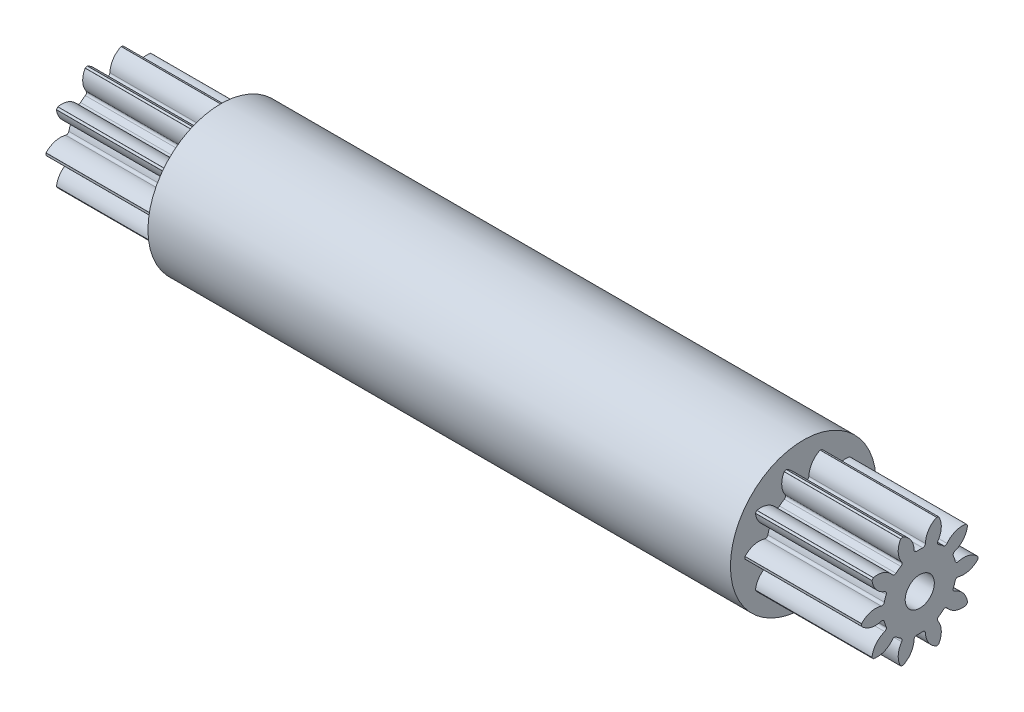
SolidWorks part; units mm, degrees
ref_plane "Plane1" through (0, 0, 0) normal (0, 0, 1) x (1, 0, 0)
ref_plane "Plane2" through (0, 0, 0) normal (0, 1, 0) x (1, 0, 0)
ref_plane "Plane3" through (0, 0, 0) normal (1, 0, 0) x (0, 0, -1)
sketch "HoldingSke" plane through (0, 0, 0) normal (0, 1, 0) x (1, 0, 0)
  line L0 (0, 0) -> (0.9848, -0.1736)
  line L1 (-15, 0) -> (100, 0) construction
  line L2 (0, 0) -> (-2.1039, 2.3779)
  line L3 (0, 0) -> (-11.863, 4.5341)
  line L4 (0, 0) -> (8.5048, 1.4996)
  line L5 (0, 0) -> (-46.8476, -17.4728)
  line L6 (0, 0) -> (-9.9476, -6.7116)
  line L7 (-2.1039, 2.3779) -> (8.6586, 51.2059)
  line L8 (-76.2, 54.61) -> (-76.1, 54.61)
  line L9 (-71.009, 38.7566) -> (-53.1078, 45.2721)
  line L10 (-76.2, 71.12) -> (104.1128, 71.12)
  line L11 (0, 0) -> (-12, 0)
  line L12 (-76.2, 101.6) -> (-76.162, 101.6)
  line L13 (24.9733, 27.94) -> (52.9518, 28.4284)
  line L14 (24.9733, 27.94) -> (24.9743, 27.94)
  line L15 (24.9733, 27.94) -> (100.4006, 29.5858)
  line L16 (-63.627, -1) -> (-12.827, -1)
  circle A0 centre (0, 0) radius 0.4
  circle A1 centre (0, 0) radius 3.749
  circle A2 centre (0, 0) radius 37.5
  circle A3 centre (0, 0) radius 0.4
  dimension "MHD" = 7.498
  dimension "Hub_dia" = 75
  dimension "Bore" = 0.8
  dimension "MBD" = 0.8
  dimension "Num_teeth" = 10
  dimension "Pitch" = 1
  dimension "Overall_len" = 50
  dimension "Show_teeth" = 10
  dimension "Thickness" = 12
  dimension "OAL" = 50.0001
  dimension "T_dim" = 0.1
  dimension "Ap" = 20
  dimension "H" = 19.05
  dimension "Pitch_radius" = 180.3128
  dimension "Width" = 12
  dimension "Backlash" = 0.038
  dimension "Addendum_fac" = 1
  dimension "Dedendum_fac" = 1.25
  dimension "Clearance_fac" = 0.25
  dimension "Dedendum_add" = 0.001
  dimension "Module" = 1
sketch "BasProSke" plane through (0, 0, 0) normal (0, 1, 0) x (1, 0, 0)
  line L0 (-10, 0) -> (60, 0) construction
  line L1 (0, 0) -> (0, 6)
  line L2 (0, 0) -> (12, 0)
  line L3 (12, 0) -> (12, 6)
  line L4 (12, 6) -> (0, 6)
  dimension "Thickness" = 12
  dimension "Diameter" = 12
revolve "Base-Revolve" add sketch "BasProSke" angle 360 about L0
sketch "TooCutSke" plane through (0, 0, 0) normal (1, 0, 0) x (0, 0, -1)
  line L1 (0, 0) -> (0, 107) construction
  line L2 (0, 0) -> (-0.8485, 4.9275) construction
  line L3 (0, 0) -> (-3.0584, 9.4126) construction
  line L4 (-0.8485, 4.9275) -> (-1.5292, 4.7063) construction
  arc A0 (0.5928, 3.7018) -> (-0.5928, 3.7018) centre (0, 0) ccw
  arc A1 (1.7758, 5.7578) -> (-1.7758, 5.7578) centre (0, 0) ccw
  circle A2 centre (0, 0) radius 5 construction
  circle A3 centre (0, 0) radius 4.6985 construction
  arc A4 (-0.5928, 3.7018) -> (-1.7758, 5.7578) centre (-2.5801, 3.9267) ccw
  arc A5 (1.7758, 5.7578) -> (0.5928, 3.7018) centre (2.5801, 3.9267) ccw
  dimension "Root_dia" = 7.498
  dimension "Overcut_dia" = 12.0508
  dimension "Pitch_dia" = 10
  dimension "Base_dia" = 9.3969
  dimension "Flank_rad" = 2
  dimension "Half_ang" = 18
  dimension "Half_CT" = 0.7157
extrude "ToothCut" cut sketch "TooCutSke" along normal through all
fillet "Breaks" radius 0.02 2 edges at (6, 5.742, -1.7407) (6, 5.742, 1.7407)
fillet "RootFillets" radius 0.251 2 edges at (6, 3.7018, -0.5928) (6, 3.7018, 0.5928)
pattern_circular "TeethCuts" count 10 every 36 about axis through (-10, 0, 0) along (1, 0, 0) of "ToothCut", "RootFillets", "Breaks"
sketch "HubNeaOneSke" plane through (0, 0, 0) normal (-1, 0, 0) x (0, 0, 1)
  circle A0 centre (0, 0) radius 3.749
  dimension "Diameter" = 7.498
extrude "HubNearOne" [suppressed] add sketch "HubNeaOneSke" along normal blind 38.0001
sketch "HubNeaBotSke" plane through (0, 0, 0) normal (-1, 0, 0) x (0, 0, 1)
  circle A0 centre (0, 0) radius 3.749
  dimension "Diameter" = 7.498
extrude "HubNearBoth" [suppressed] add sketch "HubNeaBotSke" along normal blind 19
ref_plane "FarPln" through (12, 0, 0) normal (1, 0, 0) x (0, 0, -1)
sketch "HubFarSke" plane through (12, 0, 0) normal (1, 0, 0) x (0, 0, -1)
  circle A0 centre (0, 0) radius 3.749
  dimension "Diameter" = 7.498
extrude "HubFar" [suppressed] add sketch "HubFarSke" along normal blind 19
sketch "BorSke" plane through (0, 0, 0) normal (1, 0, 0) x (0, 0, -1)
  circle A0 centre (0, 0) radius 0.4
  dimension "Diameter" = 0.8
extrude "Bore" cut sketch "BorSke" along normal mid plane 100.0001
sketch "KeySke" plane through (0, 0, 0) normal (1, 0, 0) x (0, 0, -1)
  line L0 (-0.05, 0) -> (-0.05, 0.5)
  line L1 (-0.05, 0.5) -> (0.05, 0.5)
  line L2 (0.05, 0.5) -> (0.05, 0)
  line L3 (0, 0) -> (0, 34) construction
  line L4 (-0.05, 0) -> (0.05, 0)
  dimension "Offset" = 0.5
  dimension "Width" = 0.1
extrude "Keyway" [suppressed] cut sketch "KeySke" along normal mid plane 100.0001
pattern_circular "Keyway2" [suppressed] count 2 every 90 about axis through (-10, 0, 0) along (1, 0, 0)
sketch "Sketch1" plane through (0, 0, 0) normal (-1, 0, 0) x (0, 0, 1)
  circle A0 centre (0, 0) radius 7.5
  dimension "D1" = 15
extrude "Boss-Extrude1" add sketch "Sketch1" along normal blind 30
sketch "Sketch2" plane through (-30, 0, 0) normal (-1, 0, 0) x (0, 0, 1)
  circle A0 centre (0, 0) radius 1.5
  dimension "D1" = 3
extrude "Cut-Extrude1" cut sketch "Sketch2" against normal through all
sketch "Sketch3" plane through (12, 0, 0) normal (1, 0, 0) x (0, 0, -1)
  circle A0 centre (0, 0) radius 4.8745 construction
  dimension "D1" = 9.749
mirror "Mirror1" about plane through (-30, 0, 0) normal (-1, 0, 0) of bodies 107
sketch "Sketch4" plane through (-72, 0, 0) normal (-1, 0, 0) x (0, 0, 1)
  circle A0 centre (0, 0) radius 4.8745
  dimension "D1" = 9.749
equation "' \"Module@HoldingSke\" = 6.35"
equation "' \"Num_teeth@HoldingSke\" = 12"
equation "' \"Ap@HoldingSke\" =  20"
equation "' \"Ap@HoldingSke\" = 20"
equation "' \"Width@HoldingSke\" = 0.5 * 25.4"
equation "' \"Hub_dia@HoldingSke\"= 1 * 25.4"
equation "' \"Hub_dia@HoldingSke\" = 1 * 25.4"
equation "' \"Overall_len@HoldingSke\" = 1.0 * 25.4"
equation "' \"Bore@HoldingSke\" = 0.75 * 25.4"
equation "' \"T_dim@HoldingSke\" = 0.1 * 25.4"
equation "' \"Width@KeySke\" = 0.25 * 25.4"
equation "' \"Show_teeth@HoldingSke\" = 13"
equation "' \"Backlash@HoldingSke\" = 0.009 * 25.4"
equation "' \"Addendum_fac@HoldingSke\" = 1.0"
equation "' \"Dedendum_fac@HoldingSke\" = 1.25"
equation "' \"Dedendum_add@HoldingSke\" = 0.00005 * 25.4"
equation "' \"Clearance_fac@HoldingSke\" = 0.25"
equation "\"Pitch@HoldingSke\" = 1 / \"Module@HoldingSke\""
equation "\"Overcut_dia@TooCutSke\" = (\"Num_teeth@HoldingSke\" + 2 * \"Addendum_fac@HoldingSke\") / \"Pitch@HoldingSke\" + 0.002 * 25.4"
equation "\"Pitch_dia@TooCutSke\" = \"Num_teeth@HoldingSke\" / \"Pitch@HoldingSke\""
equation "\"Base_dia@TooCutSke\" = \"Num_teeth@HoldingSke\" / \"Pitch@HoldingSke\" * cos((\"Ap@HoldingSke\"  * 3.14159265 / 180))"
equation "\"Root_dia@TooCutSke\" = (\"Num_teeth@HoldingSke\" + 2) / \"Pitch@HoldingSke\" - 2 * (\"Addendum_fac@HoldingSke\" + \"Dedendum_fac@HoldingSke\") / \"Pitch@HoldingSke\" - \"Dedendum_add@HoldingSke\" * 2"
equation "\"Half_ang@TooCutSke\" = 180 / \"Num_teeth@HoldingSke\""
equation "\"Half_CT@TooCutSke\" = \"Num_teeth@HoldingSke\" / \"Pitch@HoldingSke\" * sin((3.14159265 / 2 / \"Num_teeth@HoldingSke\")) / 2 - 7 * \"Backlash@HoldingSke\" / 4"
equation "\"Flank_rad@TooCutSke\" = \"Num_teeth@HoldingSke\" / \"Pitch@HoldingSke\" / 5"
equation "\"Radius@RootFillets\" = \"Clearance_fac@HoldingSke\" / \"Pitch@HoldingSke\" + \"Dedendum_add@HoldingSke\""
equation "\"Break_rad@Breaks\" = 0.02 / \"Pitch@HoldingSke\""
equation "\"Thickness@HoldingSke\" = \"Width@HoldingSke\""
equation "\"OAL@HoldingSke\" = \"Thickness@HoldingSke\""
equation "\"MHD@HoldingSke\" = (\"Num_teeth@HoldingSke\" + 2) / \"Pitch@HoldingSke\" - 2 * (\"Addendum_fac@HoldingSke\" + \"Dedendum_fac@HoldingSke\")  / \"Pitch@HoldingSke\" - \"Dedendum_add@HoldingSke\" * 2"
equation "\"MBD@HoldingSke\" = (\"Num_teeth@HoldingSke\" + 2) / \"Pitch@HoldingSke\" - 2 * (\"Addendum_fac@HoldingSke\" + \"Dedendum_fac@HoldingSke\")  / \"Pitch@HoldingSke\" - \"Dedendum_add@HoldingSke\" * 2 - 0.002 * 25.4"
equation "\"MHD@HoldingSke\" = ((sgn( \"MHD@HoldingSke\" - \"Hub_dia@HoldingSke\" )-1)*( \"MHD@HoldingSke\" - \"Hub_dia@HoldingSke\" ))/-2+ \"Hub_dia@HoldingSke\""
equation "\"MBD@HoldingSke\" = ((sgn( \"MBD@HoldingSke\" - \"Bore@HoldingSke\" )-1)*( \"MBD@HoldingSke\" - \"Bore@HoldingSke\" ))/-2+ \"Bore@HoldingSke\""
equation "\"OAL@HoldingSke\" = ((sgn( \"OAL@HoldingSke\" - \"Overall_len@HoldingSke\" )+1)*( \"OAL@HoldingSke\" - \"Overall_len@HoldingSke\" ))/2 + \"Overall_len@HoldingSke\" + 0.000002 * 25.4"
equation "\"Num_teeth@TeethCuts\" = int( \"Show_teeth@HoldingSke\" ) + 1"
equation "\"Num_teeth@TeethCuts\" = ((sgn( \"Num_teeth@TeethCuts\" - \"Num_teeth@HoldingSke\" )-1)*( \"Num_teeth@TeethCuts\" - \"Num_teeth@HoldingSke\" ))/-2+ \"Num_teeth@HoldingSke\""
equation "\"Num_teeth@TeethCuts\" = ((sgn( \"Num_teeth@TeethCuts\" - 2.0)+1)*( \"Num_teeth@TeethCuts\" - 2.0))/2 +2.0"
equation "\"Angle@TeethCuts\" = 360.0 / \"Num_teeth@HoldingSke\""
equation "\"Diameter@BasProSke\" = (\"Num_teeth@HoldingSke\" + 2 * \"Addendum_fac@HoldingSke\") / \"Pitch@HoldingSke\""
equation "\"Thickness@BasProSke\"  = \"Thickness@HoldingSke\""
equation "' \"Fillet_rad@BasProSke\" =  \"Thickness@HoldingSke\" * 0.05"
equation "' \"Fillet_rad@BasProSke\" = \"Thickness@HoldingSke\" * 0.05"
equation "\"MHD@HoldingSke\" = ((sgn( \"MHD@HoldingSke\" - \"Root_dia@TooCutSke\" )-1)*( \"MHD@HoldingSke\" - \"Root_dia@TooCutSke\" ))/-2+ \"Root_dia@TooCutSke\""
equation "\"Diameter@HubNeaOneSke\" = \"MHD@HoldingSke\""
equation "\"Length@HubNearOne\" = \"OAL@HoldingSke\" - \"Thickness@BasProSke\""
equation "\"Diameter@HubNeaBotSke\" = \"MHD@HoldingSke\""
equation "\"Length@HubNearBoth\" = ( \"OAL@HoldingSke\" - \"Thickness@BasProSke\" ) / 2.0"
equation "\"Thickness@FarPln\" = \"Thickness@BasProSke\""
equation "\"Diameter@HubFarSke\" = \"MHD@HoldingSke\""
equation "\"Length@HubFar\" = ( \"OAL@HoldingSke\" - \"Thickness@BasProSke\" ) / 2.0"
equation "\"Diameter@BorSke\" = \"MBD@HoldingSke\""
equation "\"D1@Bore\" = \"OAL@HoldingSke\" * 2.0"
equation "\"D1@Keyway\" = \"OAL@HoldingSke\" * 2.0"
equation "\"Offset@KeySke\" = \"T_dim@HoldingSke\" + \"MBD@HoldingSke\" / 2.0"
